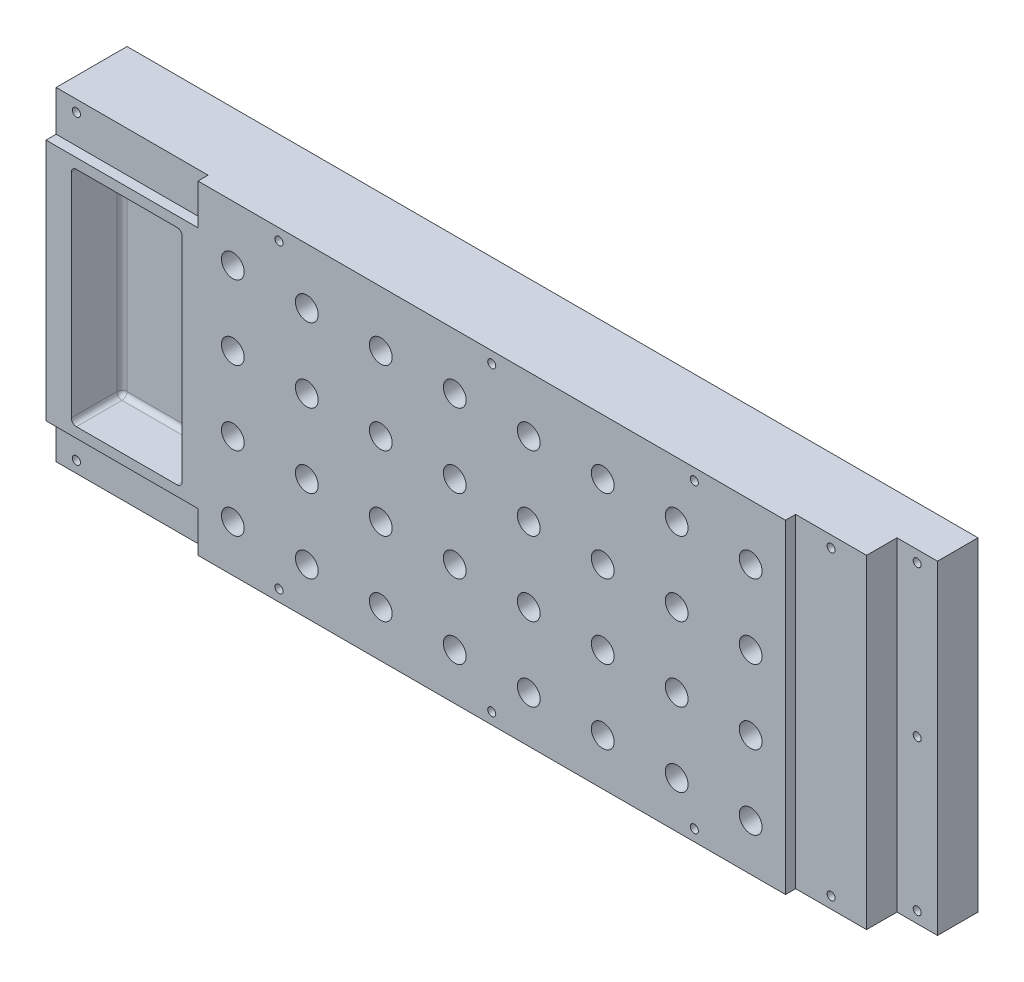
SolidWorks part; units mm, degrees
ref_plane "Front Plane" through (0, 0, 0) normal (0, 0, 1) x (1, 0, 0)
ref_plane "Top Plane" through (0, 0, 0) normal (0, 1, 0) x (1, 0, 0)
ref_plane "Right Plane" through (0, 0, 0) normal (1, 0, 0) x (0, 0, -1)
sketch "Sketch1" plane through (0, 0, 0) normal (0, 0, 1) x (1, 0, 0)
  line L0 (-64, 32) -> (-88, 32)
  line L1 (-64, -32) -> (64, -32)
  line L2 (-64, -32) -> (-64, 32) construction
  line L3 (-64, 32) -> (64, 32)
  line L4 (64, -32) -> (64, 32) construction
  line L5 (-64, -32) -> (64, 32) construction
  line L6 (-64, 32) -> (64, -32) construction
  line L7 (-88, 32) -> (-88, -32)
  line L8 (-88, -32) -> (-64, -32)
  line L9 (64, 32) -> (80, 32)
  line L10 (80, 32) -> (80, -32)
  line L11 (80, -32) -> (64, -32)
  point P0 (0, 0)
  dimension "D1" = 128
  dimension "D2" = 64
  dimension "D3" = 24
  dimension "D4" = 16
extrude "Base" add sketch "Sketch1" along normal mid plane 16
sketch "Sketch 2" plane through (0, 0, 8) normal (0, 0, 1) x (1, 0, 0)
  line L4 (-64, 31.865) -> (-64, -32.0136) construction
  line L5 (-64, -32.0136) -> (64, -32.0136) construction
  line L6 (64, -32.0136) -> (64, 32) construction
  line L7 (64, 32) -> (-64, 31.865) construction
  circle A0 centre (-51.1175, -22.8136) radius 2.25
  circle A1 centre (-36.5125, -22.8136) radius 2.25
  circle A2 centre (-21.9075, -22.8136) radius 2.25
  circle A3 centre (-7.3025, -22.8136) radius 2.25
  circle A4 centre (7.3025, -22.8136) radius 2.25
  circle A5 centre (21.9075, -22.8136) radius 2.25
  circle A6 centre (36.5125, -22.8136) radius 2.25
  circle A7 centre (51.1175, -22.8136) radius 2.25
  circle A8 centre (-36.5125, -8.2086) radius 2.25
  circle A9 centre (-21.9075, -8.2086) radius 2.25
  circle A10 centre (-7.3025, -8.2086) radius 2.25
  circle A11 centre (7.3025, -8.2086) radius 2.25
  circle A12 centre (21.9075, -8.2086) radius 2.25
  circle A13 centre (36.5125, -8.2086) radius 2.25
  circle A14 centre (51.1175, -8.2086) radius 2.25
  circle A15 centre (-36.5125, 6.3964) radius 2.25
  circle A16 centre (-21.9075, 6.3964) radius 2.25
  circle A17 centre (-7.3025, 6.3964) radius 2.25
  circle A18 centre (7.3025, 6.3964) radius 2.25
  circle A19 centre (21.9075, 6.3964) radius 2.25
  circle A20 centre (36.5125, 6.3964) radius 2.25
  circle A21 centre (51.1175, 6.3964) radius 2.25
  circle A22 centre (-36.5125, 21.0014) radius 2.25
  circle A23 centre (-21.9075, 21.0014) radius 2.25
  circle A24 centre (-7.3025, 21.0014) radius 2.25
  circle A25 centre (7.3025, 21.0014) radius 2.25
  circle A26 centre (21.9075, 21.0014) radius 2.25
  circle A27 centre (36.5125, 21.0014) radius 2.25
  circle A28 centre (51.1175, 21.0014) radius 2.25
  circle A29 centre (-51.1175, -8.2086) radius 2.25
  circle A30 centre (-51.1175, 6.3964) radius 2.25
  circle A31 centre (-51.1175, 21.0014) radius 2.25
  dimension "D1" = 9.2
  dimension "D3" = 4.5
  dimension "D6" = 14.605
  dimension "D2" = 12.8825
  dimension "D7" = 14.605
  dimension "D8" = 10.985
  dimension "D9" = 12.8825
  dimension "D4" = 8
  dimension "D5" = 4
extrude "Food Wells" cut sketch "Sketch 2" against normal blind 10
sketch "Sketch3" plane through (0, 0, -8) normal (0, 0, -1) x (-1, 0, 0)
  line L0 (88, -32) -> (-80, -32) construction
  line L2 (-80, 32) -> (88, 32) construction
  line L5 (-64, 32) -> (64, 32) construction
  line L6 (-64, 32) -> (-64, -32) construction
  line L7 (-64, -32) -> (64, -32) construction
  line L8 (64, 32) -> (64, -32) construction
  line L9 (88, 32) -> (88, -32) construction
  circle A0 centre (-60, -28) radius 2.5
  circle A1 centre (-52, -28) radius 2.5
  circle A2 centre (-44, -28) radius 2.5
  circle A3 centre (-36, -28) radius 2.5
  circle A4 centre (-28, -28) radius 2.5
  circle A5 centre (-20, -28) radius 2.5
  circle A6 centre (-12, -28) radius 2.5
  circle A7 centre (-4, -28) radius 2.5
  circle A8 centre (4, -28) radius 2.5
  circle A9 centre (12, -28) radius 2.5
  circle A10 centre (20, -28) radius 2.5
  circle A11 centre (28, -28) radius 2.5
  circle A12 centre (36, -28) radius 2.5
  circle A13 centre (44, -28) radius 2.5
  circle A14 centre (52, -28) radius 2.5
  circle A15 centre (60, -28) radius 2.5
  circle A16 centre (-52, -20) radius 2.5
  circle A17 centre (-44, -20) radius 2.5
  circle A18 centre (-36, -20) radius 2.5
  circle A19 centre (-28, -20) radius 2.5
  circle A20 centre (-20, -20) radius 2.5
  circle A21 centre (-12, -20) radius 2.5
  circle A22 centre (-4, -20) radius 2.5
  circle A23 centre (4, -20) radius 2.5
  circle A24 centre (12, -20) radius 2.5
  circle A25 centre (20, -20) radius 2.5
  circle A26 centre (28, -20) radius 2.5
  circle A27 centre (36, -20) radius 2.5
  circle A28 centre (44, -20) radius 2.5
  circle A29 centre (52, -20) radius 2.5
  circle A30 centre (60, -20) radius 2.5
  circle A31 centre (-52, -12) radius 2.5
  circle A32 centre (-44, -12) radius 2.5
  circle A33 centre (-36, -12) radius 2.5
  circle A34 centre (-28, -12) radius 2.5
  circle A35 centre (-20, -12) radius 2.5
  circle A36 centre (-12, -12) radius 2.5
  circle A37 centre (-4, -12) radius 2.5
  circle A38 centre (4, -12) radius 2.5
  circle A39 centre (12, -12) radius 2.5
  circle A40 centre (20, -12) radius 2.5
  circle A41 centre (28, -12) radius 2.5
  circle A42 centre (36, -12) radius 2.5
  circle A43 centre (44, -12) radius 2.5
  circle A44 centre (52, -12) radius 2.5
  circle A45 centre (60, -12) radius 2.5
  circle A46 centre (-52, -4) radius 2.5
  circle A47 centre (-44, -4) radius 2.5
  circle A48 centre (-36, -4) radius 2.5
  circle A49 centre (-28, -4) radius 2.5
  circle A50 centre (-20, -4) radius 2.5
  circle A51 centre (-12, -4) radius 2.5
  circle A52 centre (-4, -4) radius 2.5
  circle A53 centre (4, -4) radius 2.5
  circle A54 centre (12, -4) radius 2.5
  circle A55 centre (20, -4) radius 2.5
  circle A56 centre (28, -4) radius 2.5
  circle A57 centre (36, -4) radius 2.5
  circle A58 centre (44, -4) radius 2.5
  circle A59 centre (52, -4) radius 2.5
  circle A60 centre (60, -4) radius 2.5
  circle A61 centre (-52, 4) radius 2.5
  circle A62 centre (-44, 4) radius 2.5
  circle A63 centre (-36, 4) radius 2.5
  circle A64 centre (-28, 4) radius 2.5
  circle A65 centre (-20, 4) radius 2.5
  circle A66 centre (-12, 4) radius 2.5
  circle A67 centre (-4, 4) radius 2.5
  circle A68 centre (4, 4) radius 2.5
  circle A69 centre (12, 4) radius 2.5
  circle A70 centre (20, 4) radius 2.5
  circle A71 centre (28, 4) radius 2.5
  circle A72 centre (36, 4) radius 2.5
  circle A73 centre (44, 4) radius 2.5
  circle A74 centre (52, 4) radius 2.5
  circle A75 centre (60, 4) radius 2.5
  circle A76 centre (-52, 12) radius 2.5
  circle A77 centre (-44, 12) radius 2.5
  circle A78 centre (-36, 12) radius 2.5
  circle A79 centre (-28, 12) radius 2.5
  circle A80 centre (-20, 12) radius 2.5
  circle A81 centre (-12, 12) radius 2.5
  circle A82 centre (-4, 12) radius 2.5
  circle A83 centre (4, 12) radius 2.5
  circle A84 centre (12, 12) radius 2.5
  circle A85 centre (20, 12) radius 2.5
  circle A86 centre (28, 12) radius 2.5
  circle A87 centre (36, 12) radius 2.5
  circle A88 centre (44, 12) radius 2.5
  circle A89 centre (52, 12) radius 2.5
  circle A90 centre (60, 12) radius 2.5
  circle A91 centre (-52, 20) radius 2.5
  circle A92 centre (-44, 20) radius 2.5
  circle A93 centre (-36, 20) radius 2.5
  circle A94 centre (-28, 20) radius 2.5
  circle A95 centre (-20, 20) radius 2.5
  circle A96 centre (-12, 20) radius 2.5
  circle A97 centre (-4, 20) radius 2.5
  circle A98 centre (4, 20) radius 2.5
  circle A99 centre (12, 20) radius 2.5
  circle A100 centre (20, 20) radius 2.5
  circle A101 centre (28, 20) radius 2.5
  circle A102 centre (36, 20) radius 2.5
  circle A103 centre (44, 20) radius 2.5
  circle A104 centre (52, 20) radius 2.5
  circle A105 centre (60, 20) radius 2.5
  circle A106 centre (-52, 28) radius 2.5
  circle A107 centre (-44, 28) radius 2.5
  circle A108 centre (-36, 28) radius 2.5
  circle A109 centre (-28, 28) radius 2.5
  circle A110 centre (-20, 28) radius 2.5
  circle A111 centre (-12, 28) radius 2.5
  circle A112 centre (-4, 28) radius 2.5
  circle A113 centre (4, 28) radius 2.5
  circle A114 centre (12, 28) radius 2.5
  circle A115 centre (20, 28) radius 2.5
  circle A116 centre (28, 28) radius 2.5
  circle A117 centre (36, 28) radius 2.5
  circle A118 centre (44, 28) radius 2.5
  circle A119 centre (52, 28) radius 2.5
  circle A120 centre (60, 28) radius 2.5
  circle A121 centre (-60, -20) radius 2.5
  circle A122 centre (-60, -12) radius 2.5
  circle A123 centre (-60, -4) radius 2.5
  circle A124 centre (-60, 4) radius 2.5
  circle A125 centre (-60, 12) radius 2.5
  circle A126 centre (-60, 20) radius 2.5
  circle A127 centre (-60, 28) radius 2.5
  circle A128 centre (-52, 28) radius 2.5
  circle A129 centre (-60, 28) radius 2.5
  circle A130 centre (-68, 28) radius 2.5
  circle A131 centre (-76, 28) radius 2.5
  circle A132 centre (-60, 20) radius 2.5
  circle A133 centre (-68, 20) radius 2.5
  circle A134 centre (-76, 20) radius 2.5
  circle A135 centre (-60, 12) radius 2.5
  circle A136 centre (-68, 12) radius 2.5
  circle A137 centre (-76, 12) radius 2.5
  circle A138 centre (-60, 4) radius 2.5
  circle A139 centre (-68, 4) radius 2.5
  circle A140 centre (-76, 4) radius 2.5
  circle A141 centre (-60, -4) radius 2.5
  circle A142 centre (-68, -4) radius 2.5
  circle A143 centre (-76, -4) radius 2.5
  circle A144 centre (-60, -12) radius 2.5
  circle A145 centre (-68, -12) radius 2.5
  circle A146 centre (-76, -12) radius 2.5
  circle A147 centre (-60, -20) radius 2.5
  circle A148 centre (-68, -20) radius 2.5
  circle A149 centre (-76, -20) radius 2.5
  circle A150 centre (-60, -28) radius 2.5
  circle A151 centre (-68, -28) radius 2.5
  circle A152 centre (-76, -28) radius 2.5
  circle A153 centre (-52, 20) radius 2.5
  circle A154 centre (-52, 12) radius 2.5
  circle A155 centre (-52, 4) radius 2.5
  circle A156 centre (-52, -4) radius 2.5
  circle A157 centre (-52, -12) radius 2.5
  circle A158 centre (-52, -20) radius 2.5
  circle A159 centre (-52, -28) radius 2.5
  circle A160 centre (68, -28) radius 2.5
  circle A161 centre (76, -28) radius 2.5
  circle A162 centre (84, -28) radius 2.5
  circle A164 centre (76, -20) radius 2.5
  circle A165 centre (84, -20) radius 2.5
  circle A167 centre (76, -12) radius 2.5
  circle A168 centre (84, -12) radius 2.5
  circle A170 centre (76, -4) radius 2.5
  circle A171 centre (84, -4) radius 2.5
  circle A173 centre (76, 4) radius 2.5
  circle A174 centre (84, 4) radius 2.5
  circle A176 centre (76, 12) radius 2.5
  circle A177 centre (84, 12) radius 2.5
  circle A179 centre (76, 20) radius 2.5
  circle A180 centre (84, 20) radius 2.5
  circle A182 centre (76, 28) radius 2.5
  circle A183 centre (84, 28) radius 2.5
  circle A185 centre (68, -20) radius 2.5
  circle A186 centre (68, -12) radius 2.5
  circle A187 centre (68, -4) radius 2.5
  circle A188 centre (68, 4) radius 2.5
  circle A189 centre (68, 12) radius 2.5
  circle A190 centre (68, 20) radius 2.5
  circle A191 centre (68, 28) radius 2.5
  dimension "D3" = 16
  dimension "D5" = 4
  dimension "D9" = 5
  dimension "D10" = 8
  dimension "D11" = 4
  dimension "D13" = 8
  dimension "D14" = 3
  dimension "D16" = 4
  dimension "D1" = 4
  dimension "D2" = 4
  dimension "D6" = 4
  dimension "D8" = 8
  dimension "D4" = 8
  dimension "D12" = 8
  dimension "D15" = 8
extrude "Lego Holes" cut sketch "Sketch3" against normal blind 2
sketch "Sketch7" plane through (0, 0, 8) normal (0, 0, 1) x (1, 0, 0)
  line L1 (-88, 32) -> (96, 32) construction
  line L2 (-88, 32) -> (-88, -32) construction
  line L3 (-88, -32) -> (80, -32) construction
  line L5 (-64, 32) -> (64, 32) construction
  line L6 (-64, 32) -> (-64, -32) construction
  line L7 (-64, -32) -> (64, -32) construction
  line L15 (0, 0) -> (0, 20.7465) construction
  line L16 (0.3783, 0) -> (50000.3783, 0) construction
  line L28 (-61.1175, -22) -> (-83, -22)
  line L29 (-61.1175, -22) -> (-61.1175, 22)
  line L30 (-61.1175, 22) -> (-83, 22)
  line L31 (-83, -22) -> (-83, 22)
  line L32 (-61.1175, -22) -> (-83, 22) construction
  line L33 (-61.1175, 22) -> (-83, -22) construction
  point P22 (-72.0587, 0)
  dimension "D1" = 10
  dimension "D2" = 10
  dimension "D3" = 5
  dimension "D4" = 10
extrude "Hydration Wells" cut sketch "Sketch7" against normal blind 10
fillet "Food Wells Fillet" radius 1 8 edges at (-83, 0, -2) (-72.0587, -22, -2) (-61.1175, 0, -2) (-72.0587, 22, -2) (-83, -22, 3) (-61.1175, -22, 3) (-61.1175, 22, 3) (-83, 22, 3)
sketch "Sketch8" plane through (0, -32, 0) normal (0, -1, 0) x (1, 0, 0)
  line L6 (80, 8) -> (72, 8)
  line L8 (80, 8) -> (80, 0)
  line L10 (80, 0) -> (72, 0)
  line L11 (72, 8) -> (72, 0)
  dimension "D1" = 8
  dimension "D2" = 8
extrude "Divet" cut sketch "Sketch8" against normal through all and the other way through all
sketch "Sketch45" plane through (0, 0, 8) normal (0, 0, 1) x (1, 0, 0)
  line L0 (72, 32) -> (-88, 32) construction
  line L1 (58, 32) -> (73, 32)
  line L2 (58, 32) -> (58, -32)
  line L3 (58, -32) -> (73, -32)
  line L4 (73, 32) -> (73, -32)
  line L5 (80, -32) -> (72, -32) construction
  line L6 (80, 32) -> (80, -32) construction
  line L8 (-88, 32) -> (-58, 32)
  line L9 (-88, 32) -> (-88, 24)
  line L10 (-88, 24) -> (-58, 24)
  line L11 (-58, 32) -> (-58, 24)
  line L12 (-88, -32) -> (-58, -32)
  line L13 (-88, -32) -> (-88, -24)
  line L14 (-88, -24) -> (-58, -24)
  line L15 (-58, -32) -> (-58, -24)
  dimension "D1" = 7
  dimension "D2" = 15
  dimension "D3" = 30
  dimension "D4" = 8
extrude "Slider Helper" cut sketch "Sketch45" against normal blind 2
sketch "Sketch6" plane through (0, 0, 8) normal (0, 0, 1) x (1, 0, 0)
  line L0 (0, 0) -> (0, 50000) construction
  line L1 (-84, -29.75) -> (76, -29.75) construction
  line L2 (-58, -32) -> (58, -32) construction
  line L4 (58, 32) -> (-58, 32) construction
  line L5 (-84, 29.75) -> (76, 29.75) construction
  line L7 (-64, 32) -> (64, 32) construction
  line L8 (-64, 32) -> (-64, -32) construction
  line L9 (-64, -32) -> (64, -32) construction
  line L11 (-88, 32) -> (80, 32) construction
  line L13 (-88, -32) -> (80, -32) construction
  circle A4 centre (0, -29.75) radius 0.7937
  circle A5 centre (0, 29.75) radius 0.7937
  circle A6 centre (-42, 29.75) radius 0.7937
  circle A7 centre (-42, -29.75) radius 0.7937
  circle A8 centre (40, 29.75) radius 0.7937
  circle A9 centre (40, -29.75) radius 0.7937
  dimension "D3" = 2.25
  dimension "D5" = 42
  dimension "D7" = 2.25
  dimension "D10" = 1.5875
  dimension "D11" = 40
  dimension "D12" = 1.5875
  dimension "D16" = 1.5875
  dimension "D18" = 1.5875
  dimension "D20" = 1.5875
  dimension "D21" = 1.5875
  dimension "D2" = 2.25
  dimension "D4" = 42
  dimension "D8" = 40
extrude "Magnet Holes (main)" cut sketch "Sketch6" against normal blind 4.5
sketch "Sketch9" plane through (0, 0, 0) normal (0, 0, 1) x (1, 0, 0)
  line L0 (80, 32) -> (80, -32) construction
  line L1 (80, 20.3919) -> (80, -49979.6067) construction
  line L6 (85.514, 32) -> (50085.514, 32) construction
  line L8 (79.6518, -31.9991) -> (50079.6518, -31.9991) construction
  circle A0 centre (76, 29.75) radius 0.7937
  circle A1 centre (76, -29.7491) radius 0.7937
  circle A2 centre (76, 0) radius 0.7937
  dimension "D3" = 1.5875
  dimension "D4" = 4
  dimension "D6" = 1.5875
  dimension "D7" = 4
  dimension "D9" = 1.5875
  dimension "D1" = 2.25
  dimension "D2" = 4
  dimension "D5" = 2.25
  dimension "D8" = 32
extrude "Magnet Holes (divet)" cut sketch "Sketch9" against normal blind 4.5
sketch "Sketch43" plane through (0, 0, 6) normal (0, 0, 1) x (1, 0, 0)
  line L3 (0, 0) -> (0, 49.7712) construction
  line L4 (17.7509, 29.75) -> (50017.7509, 29.75) construction
  line L5 (23.2628, -29.75) -> (50023.2628, -29.75) construction
  line L6 (72, 32) -> (58, 32) construction
  line L7 (58, -32) -> (72, -32) construction
  line L8 (-88, 24) -> (-88, -24) construction
  line L9 (72, -32) -> (72, 32) construction
  circle A2 centre (65, 29.75) radius 0.7937
  circle A3 centre (65, -29.75) radius 0.7937
  circle A4 centre (-84, -29.75) radius 0.7937
  circle A5 centre (-84, 29.75) radius 0.7937
  dimension "D5" = 1.5875
  dimension "D1" = 2.25
  dimension "D2" = 2.25
  dimension "D3" = 4
  dimension "D4" = 7
extrude "Magnet Holes (helper)" cut sketch "Sketch43" against normal blind 4.5
sketch "Sketch46" plane through (0, -32, 0) normal (0, -1, 0) x (1, 0, 0)
  line L0 (0, 0) -> (0, 50000) construction
  line L1 (-74.9834, -4) -> (52.1185, -4) construction
  line L2 (-88, -8) -> (80, -8) construction
  line L3 (-88, 6) -> (-88, -8) construction
  circle A0 centre (-84, -4) radius 2.5
  circle A1 centre (-76, -4) radius 2.5
  circle A2 centre (-68, -4) radius 2.5
  circle A3 centre (-60, -4) radius 2.5
  circle A4 centre (-52, -4) radius 2.5
  circle A5 centre (-44, -4) radius 2.5
  circle A6 centre (-36, -4) radius 2.5
  circle A7 centre (-28, -4) radius 2.5
  circle A8 centre (-20, -4) radius 2.5
  circle A9 centre (-12, -4) radius 2.5
  circle A10 centre (-4, -4) radius 2.5
  circle A11 centre (4, -4) radius 2.5
  circle A12 centre (12, -4) radius 2.5
  circle A13 centre (20, -4) radius 2.5
  circle A14 centre (28, -4) radius 2.5
  circle A15 centre (36, -4) radius 2.5
  circle A16 centre (44, -4) radius 2.5
  circle A17 centre (52, -4) radius 2.5
  circle A18 centre (60, -4) radius 2.5
  circle A19 centre (68, -4) radius 2.5
  circle A20 centre (76, -4) radius 2.5
  circle A21 centre (-76, 4) radius 2.5
  circle A22 centre (-68, 4) radius 2.5
  circle A23 centre (-60, 4) radius 2.5
  circle A24 centre (-52, 4) radius 2.5
  circle A25 centre (-44, 4) radius 2.5
  circle A26 centre (-36, 4) radius 2.5
  circle A27 centre (-28, 4) radius 2.5
  circle A28 centre (-20, 4) radius 2.5
  circle A29 centre (-12, 4) radius 2.5
  circle A30 centre (-4, 4) radius 2.5
  circle A31 centre (4, 4) radius 2.5
  circle A32 centre (12, 4) radius 2.5
  circle A33 centre (20, 4) radius 2.5
  circle A34 centre (28, 4) radius 2.5
  circle A35 centre (36, 4) radius 2.5
  circle A36 centre (44, 4) radius 2.5
  circle A37 centre (52, 4) radius 2.5
  circle A38 centre (60, 4) radius 2.5
  circle A39 centre (68, 4) radius 2.5
  circle A40 centre (76, 4) radius 2.5
  circle A41 centre (-84, 4) radius 2.5
  dimension "D2" = 4
  dimension "D3" = 21
  dimension "D1" = 4
  dimension "D4" = 2
